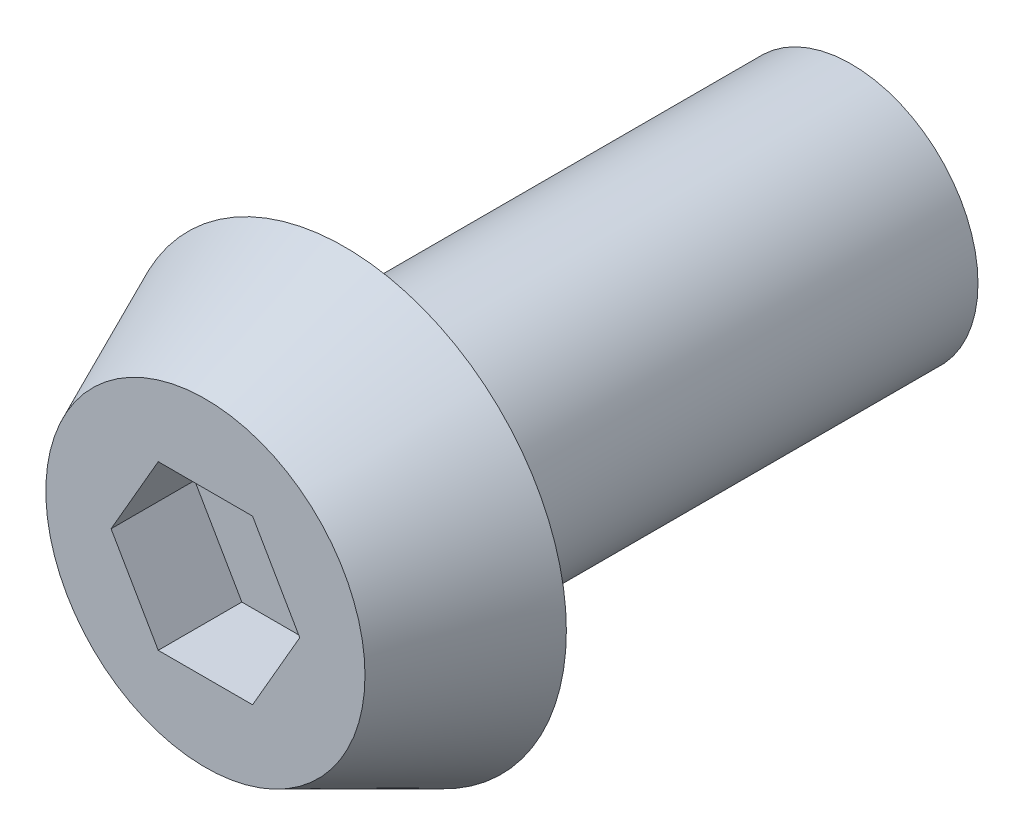
SolidWorks part; units mm, degrees
ref_plane "Front Plane" through (0, 0, 0) normal (0, 0, 1) x (1, 0, 0)
ref_plane "Top Plane" through (0, 0, 0) normal (0, 1, 0) x (1, 0, 0)
ref_plane "Right Plane" through (0, 0, 0) normal (1, 0, 0) x (0, 0, -1)
sketch "SK_shank" plane through (0, 0, 0) normal (0, 0, 1) x (1, 0, 0)
  circle A0 centre (0, 0) radius 1
extrude "Shank" add sketch "SK_shank" against normal blind 4
sketch "SK_head" plane through (0, 0, 0) normal (0, 0, 1) x (1, 0, 0)
  circle A0 centre (0, 0) radius 1.75
extrude "Head" add sketch "SK_head" along normal blind 1.1 draft 24.011
sketch "SK_socket" plane through (0, 0, 0) normal (0, 0, 1) x (1, 0, 0)
  line L0 (0.7448, 0) -> (0.3724, -0.645)
  line L1 (0.3724, -0.645) -> (-0.3724, -0.645)
  line L2 (-0.3724, -0.645) -> (-0.7448, 0)
  line L3 (-0.7448, 0) -> (-0.3724, 0.645)
  line L4 (-0.3724, 0.645) -> (0.3724, 0.645)
  line L5 (0.3724, 0.645) -> (0.7448, 0)
extrude "Socket" cut sketch "SK_socket" along normal blind 1.16 from offset 0.44
